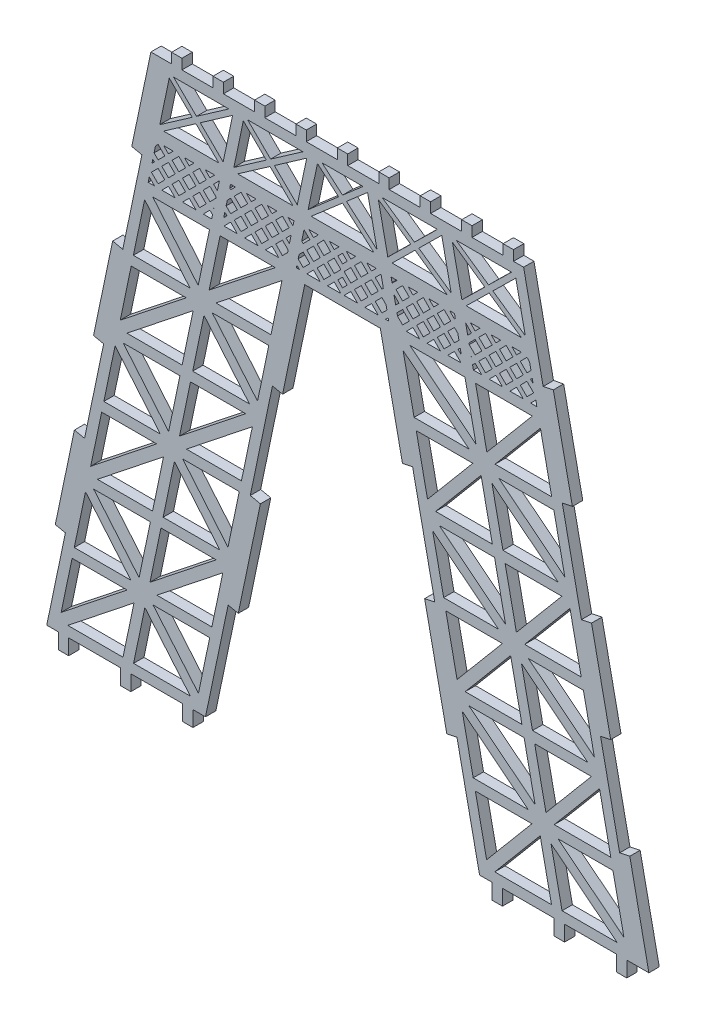
SolidWorks part; units mm, degrees
ref_plane "Front Plane" through (0, 0, 0) normal (0, 0, 1) x (1, 0, 0)
ref_plane "Top Plane" through (0, 0, 0) normal (0, 1, 0) x (1, 0, 0)
ref_plane "Right Plane" through (0, 0, 0) normal (1, 0, 0) x (0, 0, -1)
sketch "Sketch1" plane through (0, 0, 0) normal (0, 0, 1) x (1, 0, 0)
  line L2244 (350.4546, 229.6647) -> (353.6346, 244.8694)
  line L2245 (353.6346, 244.8694) -> (369.6113, 244.8694)
  line L2246 (369.6113, 244.8694) -> (350.4546, 229.6647)
  line L2247 (371.5439, 242.5732) -> (368.3725, 227.41)
  line L2248 (368.3725, 227.41) -> (352.4395, 227.41)
  line L2249 (352.4395, 227.41) -> (371.5439, 242.5732)
  line L2250 (327.9011, 224.41) -> (324.7297, 209.2469)
  line L2251 (324.7297, 209.2469) -> (343.8341, 224.41)
  line L2252 (343.8341, 224.41) -> (327.9011, 224.41)
  line L2253 (326.6623, 206.9506) -> (345.8191, 222.1554)
  line L2254 (345.8191, 222.1554) -> (342.639, 206.9506)
  line L2255 (342.639, 206.9506) -> (326.6623, 206.9506)
  line L2256 (341.8963, 188.7459) -> (345.0764, 203.9506)
  line L2257 (345.0764, 203.9506) -> (361.0531, 203.9506)
  line L2258 (361.0531, 203.9506) -> (341.8963, 188.7459)
  line L2259 (362.9857, 201.6544) -> (359.8143, 186.4912)
  line L2260 (359.8143, 186.4912) -> (343.8813, 186.4912)
  line L2261 (343.8813, 186.4912) -> (362.9857, 201.6544)
  line L2262 (319.3429, 183.4912) -> (316.1715, 168.3281)
  line L2263 (316.1715, 168.3281) -> (335.2759, 183.4912)
  line L2264 (335.2759, 183.4912) -> (319.3429, 183.4912)
  line L2265 (318.1041, 166.0318) -> (337.2608, 181.2366)
  line L2266 (337.2608, 181.2366) -> (334.0808, 166.0318)
  line L2267 (334.0808, 166.0318) -> (318.1041, 166.0318)
  line L2268 (333.3381, 147.8271) -> (336.5182, 163.0318)
  line L2269 (336.5182, 163.0318) -> (352.4949, 163.0318)
  line L2270 (352.4949, 163.0318) -> (333.3381, 147.8271)
  line L2271 (354.4274, 160.7356) -> (351.256, 145.5724)
  line L2272 (351.256, 145.5724) -> (335.3231, 145.5724)
  line L2273 (335.3231, 145.5724) -> (354.4274, 160.7356)
  line L2274 (310.7847, 142.5724) -> (307.6133, 127.4093)
  line L2275 (307.6133, 127.4093) -> (326.7177, 142.5724)
  line L2276 (326.7177, 142.5724) -> (310.7847, 142.5724)
  line L2277 (309.5459, 125.113) -> (328.7026, 140.3178)
  line L2278 (328.7026, 140.3178) -> (325.5225, 125.113)
  line L2279 (325.5225, 125.113) -> (309.5459, 125.113)
  line L2280 (345.0164, 125.113) -> (328.5875, 125.113)
  line L2281 (328.5875, 125.113) -> (331.8576, 140.7482)
  line L2282 (331.8576, 140.7482) -> (345.0164, 125.113)
  line L2283 (347.3672, 126.9789) -> (350.6286, 142.5724)
  line L2284 (350.6286, 142.5724) -> (334.2433, 142.5724)
  line L2285 (334.2433, 142.5724) -> (347.3672, 126.9789)
  line L2286 (317.0244, 163.0318) -> (333.4533, 163.0318)
  line L2287 (333.4533, 163.0318) -> (330.1832, 147.3967)
  line L2288 (330.1832, 147.3967) -> (317.0244, 163.0318)
  line L2289 (314.6736, 161.166) -> (311.4122, 145.5724)
  line L2290 (311.4122, 145.5724) -> (327.7974, 145.5724)
  line L2291 (327.7974, 145.5724) -> (314.6736, 161.166)
  line L2292 (353.5746, 166.0318) -> (337.1457, 166.0318)
  line L2293 (337.1457, 166.0318) -> (340.4158, 181.667)
  line L2294 (340.4158, 181.667) -> (353.5746, 166.0318)
  line L2295 (355.9254, 167.8977) -> (342.8016, 183.4912)
  line L2296 (342.8016, 183.4912) -> (359.1868, 183.4912)
  line L2297 (359.1868, 183.4912) -> (355.9254, 167.8977)
  line L2298 (325.5826, 203.9506) -> (342.0115, 203.9506)
  line L2299 (342.0115, 203.9506) -> (338.7414, 188.3155)
  line L2300 (338.7414, 188.3155) -> (325.5826, 203.9506)
  line L2301 (323.2318, 202.0848) -> (319.9704, 186.4912)
  line L2302 (319.9704, 186.4912) -> (336.3556, 186.4912)
  line L2303 (336.3556, 186.4912) -> (323.2318, 202.0848)
  line L2304 (362.1328, 206.9506) -> (345.7039, 206.9506)
  line L2305 (345.7039, 206.9506) -> (348.974, 222.5858)
  line L2306 (348.974, 222.5858) -> (362.1328, 206.9506)
  line L2307 (364.4836, 208.8164) -> (351.3598, 224.41)
  line L2308 (351.3598, 224.41) -> (367.745, 224.41)
  line L2309 (367.745, 224.41) -> (364.4836, 208.8164)
  line L2310 (334.1408, 244.8694) -> (350.5697, 244.8694)
  line L2311 (350.5697, 244.8694) -> (347.2996, 229.2343)
  line L2312 (347.2996, 229.2343) -> (334.1408, 244.8694)
  line L2313 (331.79, 243.0036) -> (328.5286, 227.41)
  line L2314 (328.5286, 227.41) -> (344.9138, 227.41)
  line L2315 (344.9138, 227.41) -> (331.79, 243.0036)
  line L2316 (347.8925, 270.3378) -> (357.262, 276.8665)
  line L2317 (357.262, 276.8665) -> (354.531, 263.8091)
  line L2318 (354.531, 263.8091) -> (347.8925, 270.3378)
  line L2319 (338.9138, 277.0641) -> (345.5523, 270.5354)
  line L2320 (345.5523, 270.5354) -> (336.1828, 264.0067)
  line L2321 (336.1828, 264.0067) -> (338.9138, 277.0641)
  line L2322 (353.2789, 262.9366) -> (337.2709, 262.9366)
  line L2323 (337.2709, 262.9366) -> (346.6404, 269.4653)
  line L2324 (346.6404, 269.4653) -> (353.2789, 262.9366)
  line L2325 (340.1659, 277.9366) -> (356.1739, 277.9366)
  line L2326 (356.1739, 277.9366) -> (346.8044, 271.4079)
  line L2327 (346.8044, 271.4079) -> (340.1659, 277.9366)
  line L2328 (367.0067, 270.5354) -> (357.6372, 264.0067)
  line L2329 (357.6372, 264.0067) -> (360.3682, 277.0641)
  line L2330 (360.3682, 277.0641) -> (367.0067, 270.5354)
  line L2331 (374.7333, 262.9366) -> (358.7253, 262.9366)
  line L2332 (358.7253, 262.9366) -> (368.0948, 269.4653)
  line L2333 (368.0948, 269.4653) -> (374.7333, 262.9366)
  line L2334 (369.3469, 270.3378) -> (378.7164, 276.8665)
  line L2335 (378.7164, 276.8665) -> (375.9854, 263.8091)
  line L2336 (375.9854, 263.8091) -> (369.3469, 270.3378)
  line L2337 (361.6203, 277.9366) -> (377.6283, 277.9366)
  line L2338 (377.6283, 277.9366) -> (368.2588, 271.4079)
  line L2339 (368.2588, 271.4079) -> (361.6203, 277.9366)
  line L2340 (387.9485, 271.7955) -> (379.1213, 264.1485)
  line L2341 (379.1213, 264.1485) -> (381.8294, 277.0965)
  line L2342 (381.8294, 277.0965) -> (387.9485, 271.7955)
  line L2343 (379.315, 259.3064) -> (382.0676, 259.3064)
  line L2344 (382.0676, 259.3064) -> (380.6913, 257.9301)
  line L2345 (380.6913, 257.9301) -> (379.315, 259.3064)
  line L2346 (386.6913, 257.9301) -> (385.315, 259.3064)
  line L2347 (385.315, 259.3064) -> (388.0676, 259.3064)
  line L2348 (388.0676, 259.3064) -> (386.6913, 257.9301)
  line L2349 (386.6913, 255.8088) -> (388.6306, 253.8694)
  line L2350 (388.6306, 253.8694) -> (386.6913, 251.9301)
  line L2351 (386.6913, 251.9301) -> (384.752, 253.8694)
  line L2352 (384.752, 253.8694) -> (386.6913, 255.8088)
  line L2353 (385.6306, 256.8694) -> (383.6913, 254.9301)
  line L2354 (383.6913, 254.9301) -> (381.752, 256.8694)
  line L2355 (381.752, 256.8694) -> (383.6913, 258.8088)
  line L2356 (383.6913, 258.8088) -> (385.6306, 256.8694)
  line L2357 (384.752, 247.8694) -> (386.6913, 249.8088)
  line L2358 (386.6913, 249.8088) -> (388.6306, 247.8694)
  line L2359 (388.6306, 247.8694) -> (384.752, 247.8694)
  line L2360 (381.752, 250.8694) -> (383.6913, 252.8088)
  line L2361 (383.6913, 252.8088) -> (385.6306, 250.8694)
  line L2362 (385.6306, 250.8694) -> (383.6913, 248.9301)
  line L2363 (383.6913, 248.9301) -> (381.752, 250.8694)
  line L2364 (378.752, 253.8694) -> (380.6913, 255.8088)
  line L2365 (380.6913, 255.8088) -> (382.6306, 253.8694)
  line L2366 (382.6306, 253.8694) -> (380.6913, 251.9301)
  line L2367 (380.6913, 251.9301) -> (378.752, 253.8694)
  line L2368 (373.315, 259.3064) -> (375.0436, 259.3064)
  line L2369 (375.0436, 259.3064) -> (374.7728, 258.0116)
  line L2370 (374.7728, 258.0116) -> (374.6913, 257.9301)
  line L2371 (374.6913, 257.9301) -> (373.315, 259.3064)
  line L2372 (377.2794, 255.342) -> (377.9503, 258.5498)
  line L2373 (377.9503, 258.5498) -> (379.6306, 256.8694)
  line L2374 (379.6306, 256.8694) -> (377.6913, 254.9301)
  line L2375 (377.6913, 254.9301) -> (377.2794, 255.342)
  line L2376 (376.6306, 247.8694) -> (375.7165, 247.8694)
  line L2377 (375.7165, 247.8694) -> (375.8746, 248.6255)
  line L2378 (375.8746, 248.6255) -> (376.6306, 247.8694)
  line L2379 (378.752, 247.8694) -> (380.6913, 249.8088)
  line L2380 (380.6913, 249.8088) -> (382.6306, 247.8694)
  line L2381 (382.6306, 247.8694) -> (378.752, 247.8694)
  line L2382 (376.2416, 250.3798) -> (376.5005, 251.618)
  line L2383 (376.5005, 251.618) -> (377.6913, 252.8088)
  line L2384 (377.6913, 252.8088) -> (379.6306, 250.8694)
  line L2385 (379.6306, 250.8694) -> (377.6913, 248.9301)
  line L2386 (377.6913, 248.9301) -> (376.2416, 250.3798)
  line L2387 (372.752, 253.8694) -> (374.2118, 255.3293)
  line L2388 (374.2118, 255.3293) -> (373.7068, 252.9146)
  line L2389 (373.7068, 252.9146) -> (372.752, 253.8694)
  line L2390 (369.752, 256.8694) -> (371.6913, 258.8088)
  line L2391 (371.6913, 258.8088) -> (373.6306, 256.8694)
  line L2392 (373.6306, 256.8694) -> (371.6913, 254.9301)
  line L2393 (371.6913, 254.9301) -> (369.752, 256.8694)
  line L2394 (367.315, 259.3064) -> (370.0676, 259.3064)
  line L2395 (370.0676, 259.3064) -> (368.6913, 257.9301)
  line L2396 (368.6913, 257.9301) -> (367.315, 259.3064)
  line L2397 (369.752, 250.8694) -> (371.6913, 252.8088)
  line L2398 (371.6913, 252.8088) -> (373.3399, 251.1602)
  line L2399 (373.3399, 251.1602) -> (373.186, 250.4248)
  line L2400 (373.186, 250.4248) -> (371.6913, 248.9301)
  line L2401 (371.6913, 248.9301) -> (369.752, 250.8694)
  line L2402 (366.752, 253.8694) -> (368.6913, 255.8088)
  line L2403 (368.6913, 255.8088) -> (370.6306, 253.8694)
  line L2404 (370.6306, 253.8694) -> (368.6913, 251.9301)
  line L2405 (368.6913, 251.9301) -> (366.752, 253.8694)
  line L2406 (363.752, 256.8694) -> (365.6913, 258.8088)
  line L2407 (365.6913, 258.8088) -> (367.6306, 256.8694)
  line L2408 (367.6306, 256.8694) -> (365.6913, 254.9301)
  line L2409 (365.6913, 254.9301) -> (363.752, 256.8694)
  line L2410 (361.315, 259.3064) -> (364.0676, 259.3064)
  line L2411 (364.0676, 259.3064) -> (362.6913, 257.9301)
  line L2412 (362.6913, 257.9301) -> (361.315, 259.3064)
  line L2413 (366.752, 247.8694) -> (368.6913, 249.8088)
  line L2414 (368.6913, 249.8088) -> (370.6306, 247.8694)
  line L2415 (370.6306, 247.8694) -> (366.752, 247.8694)
  line L2416 (363.752, 250.8694) -> (365.6913, 252.8088)
  line L2417 (365.6913, 252.8088) -> (367.6306, 250.8694)
  line L2418 (367.6306, 250.8694) -> (365.6913, 248.9301)
  line L2419 (365.6913, 248.9301) -> (363.752, 250.8694)
  line L2420 (360.752, 253.8694) -> (362.6913, 255.8088)
  line L2421 (362.6913, 255.8088) -> (364.6306, 253.8694)
  line L2422 (364.6306, 253.8694) -> (362.6913, 251.9301)
  line L2423 (362.6913, 251.9301) -> (360.752, 253.8694)
  line L2424 (357.752, 256.8694) -> (359.6913, 258.8088)
  line L2425 (359.6913, 258.8088) -> (361.6306, 256.8694)
  line L2426 (361.6306, 256.8694) -> (359.6913, 254.9301)
  line L2427 (359.6913, 254.9301) -> (357.752, 256.8694)
  line L2428 (356.4225, 258.1989) -> (356.6541, 259.3064)
  line L2429 (356.6541, 259.3064) -> (358.0676, 259.3064)
  line L2430 (358.0676, 259.3064) -> (356.6913, 257.9301)
  line L2431 (356.6913, 257.9301) -> (356.4225, 258.1989)
  line L2432 (355.6306, 250.8694) -> (354.6936, 249.9323)
  line L2433 (354.6936, 249.9323) -> (355.0177, 251.4823)
  line L2434 (355.0177, 251.4823) -> (355.6306, 250.8694)
  line L2435 (360.752, 247.8694) -> (362.6913, 249.8088)
  line L2436 (362.6913, 249.8088) -> (364.6306, 247.8694)
  line L2437 (364.6306, 247.8694) -> (360.752, 247.8694)
  line L2438 (357.752, 250.8694) -> (359.6913, 252.8088)
  line L2439 (359.6913, 252.8088) -> (361.6306, 250.8694)
  line L2440 (361.6306, 250.8694) -> (359.6913, 248.9301)
  line L2441 (359.6913, 248.9301) -> (357.752, 250.8694)
  line L2442 (355.3847, 253.2367) -> (355.7193, 254.8368)
  line L2443 (355.7193, 254.8368) -> (356.6913, 255.8088)
  line L2444 (356.6913, 255.8088) -> (358.6306, 253.8694)
  line L2445 (358.6306, 253.8694) -> (356.6913, 251.9301)
  line L2446 (356.6913, 251.9301) -> (355.3847, 253.2367)
  line L2447 (351.752, 256.8694) -> (353.4306, 258.5481)
  line L2448 (353.4306, 258.5481) -> (352.8499, 255.7715)
  line L2449 (352.8499, 255.7715) -> (351.752, 256.8694)
  line L2450 (349.315, 259.3064) -> (352.0676, 259.3064)
  line L2451 (352.0676, 259.3064) -> (350.6913, 257.9301)
  line L2452 (350.6913, 257.9301) -> (349.315, 259.3064)
  line L2453 (354.752, 247.8694) -> (356.6913, 249.8088)
  line L2454 (356.6913, 249.8088) -> (358.6306, 247.8694)
  line L2455 (358.6306, 247.8694) -> (354.752, 247.8694)
  line L2456 (351.752, 250.8694) -> (351.8439, 250.9613)
  line L2457 (351.8439, 250.9613) -> (351.8121, 250.8093)
  line L2458 (351.8121, 250.8093) -> (351.752, 250.8694)
  line L2459 (348.752, 253.8694) -> (350.6913, 255.8088)
  line L2460 (350.6913, 255.8088) -> (352.483, 254.0171)
  line L2461 (352.483, 254.0171) -> (352.4049, 253.6437)
  line L2462 (352.4049, 253.6437) -> (350.6913, 251.9301)
  line L2463 (350.6913, 251.9301) -> (348.752, 253.8694)
  line L2464 (345.752, 256.8694) -> (347.6913, 258.8088)
  line L2465 (347.6913, 258.8088) -> (349.6306, 256.8694)
  line L2466 (349.6306, 256.8694) -> (347.6913, 254.9301)
  line L2467 (347.6913, 254.9301) -> (345.752, 256.8694)
  line L2468 (343.315, 259.3064) -> (346.0676, 259.3064)
  line L2469 (346.0676, 259.3064) -> (344.6913, 257.9301)
  line L2470 (344.6913, 257.9301) -> (343.315, 259.3064)
  line L2471 (348.752, 247.8694) -> (350.6913, 249.8088)
  line L2472 (350.6913, 249.8088) -> (351.4451, 249.0549)
  line L2473 (351.4451, 249.0549) -> (351.1972, 247.8694)
  line L2474 (351.1972, 247.8694) -> (348.752, 247.8694)
  line L2475 (345.752, 250.8694) -> (347.6913, 252.8088)
  line L2476 (347.6913, 252.8088) -> (349.6306, 250.8694)
  line L2477 (349.6306, 250.8694) -> (347.6913, 248.9301)
  line L2478 (347.6913, 248.9301) -> (345.752, 250.8694)
  line L2479 (342.752, 253.8694) -> (344.6913, 255.8088)
  line L2480 (344.6913, 255.8088) -> (346.6306, 253.8694)
  line L2481 (346.6306, 253.8694) -> (344.6913, 251.9301)
  line L2482 (344.6913, 251.9301) -> (342.752, 253.8694)
  line L2483 (339.752, 256.8694) -> (341.6913, 258.8088)
  line L2484 (341.6913, 258.8088) -> (343.6306, 256.8694)
  line L2485 (343.6306, 256.8694) -> (341.6913, 254.9301)
  line L2486 (341.6913, 254.9301) -> (339.752, 256.8694)
  line L2487 (337.315, 259.3064) -> (340.0676, 259.3064)
  line L2488 (340.0676, 259.3064) -> (338.6913, 257.9301)
  line L2489 (338.6913, 257.9301) -> (337.315, 259.3064)
  line L2490 (342.752, 247.8694) -> (344.6913, 249.8088)
  line L2491 (344.6913, 249.8088) -> (346.6306, 247.8694)
  line L2492 (346.6306, 247.8694) -> (342.752, 247.8694)
  line L2493 (339.752, 250.8694) -> (341.6913, 252.8088)
  line L2494 (341.6913, 252.8088) -> (343.6306, 250.8694)
  line L2495 (343.6306, 250.8694) -> (341.6913, 248.9301)
  line L2496 (341.6913, 248.9301) -> (339.752, 250.8694)
  line L2497 (336.752, 253.8694) -> (338.6913, 255.8088)
  line L2498 (338.6913, 255.8088) -> (340.6306, 253.8694)
  line L2499 (340.6306, 253.8694) -> (338.6913, 251.9301)
  line L2500 (338.6913, 251.9301) -> (336.752, 253.8694)
  line L2501 (334.5278, 256.0936) -> (334.9382, 258.0556)
  line L2502 (334.9382, 258.0556) -> (335.6913, 258.8088)
  line L2503 (335.6913, 258.8088) -> (337.6306, 256.8694)
  line L2504 (337.6306, 256.8694) -> (335.6913, 254.9301)
  line L2505 (335.6913, 254.9301) -> (334.5278, 256.0936)
  line L2506 (334.1609, 254.3392) -> (334.6306, 253.8694)
  line L2507 (334.6306, 253.8694) -> (333.9124, 253.1512)
  line L2508 (333.9124, 253.1512) -> (334.1609, 254.3392)
  line L2509 (336.752, 247.8694) -> (338.6913, 249.8088)
  line L2510 (338.6913, 249.8088) -> (340.6306, 247.8694)
  line L2511 (340.6306, 247.8694) -> (336.752, 247.8694)
  line L2512 (333.752, 250.8694) -> (335.6913, 252.8088)
  line L2513 (335.6913, 252.8088) -> (337.6306, 250.8694)
  line L2514 (337.6306, 250.8694) -> (335.6913, 248.9301)
  line L2515 (335.6913, 248.9301) -> (333.752, 250.8694)
  line L2516 (332.8077, 247.8694) -> (334.6306, 247.8694)
  line L2517 (334.6306, 247.8694) -> (333.123, 249.3771)
  line L2518 (333.123, 249.3771) -> (332.8077, 247.8694)
  line L2519 (427.7333, 229.6647) -> (424.5532, 244.8694)
  line L2520 (424.5532, 244.8694) -> (408.5765, 244.8694)
  line L2521 (408.5765, 244.8694) -> (427.7333, 229.6647)
  line L2522 (425.7483, 227.41) -> (409.8153, 227.41)
  line L2523 (409.8153, 227.41) -> (406.644, 242.5732)
  line L2524 (406.644, 242.5732) -> (425.7483, 227.41)
  line L2525 (434.3537, 224.41) -> (453.4581, 209.2469)
  line L2526 (453.4581, 209.2469) -> (450.2867, 224.41)
  line L2527 (450.2867, 224.41) -> (434.3537, 224.41)
  line L2528 (451.5255, 206.9506) -> (432.3688, 222.1554)
  line L2529 (432.3688, 222.1554) -> (435.5489, 206.9506)
  line L2530 (435.5489, 206.9506) -> (451.5255, 206.9506)
  line L2531 (436.2915, 188.7459) -> (433.1114, 203.9506)
  line L2532 (433.1114, 203.9506) -> (417.1347, 203.9506)
  line L2533 (417.1347, 203.9506) -> (436.2915, 188.7459)
  line L2534 (434.3065, 186.4912) -> (418.3736, 186.4912)
  line L2535 (418.3736, 186.4912) -> (415.2022, 201.6544)
  line L2536 (415.2022, 201.6544) -> (434.3065, 186.4912)
  line L2537 (442.9119, 183.4912) -> (462.0163, 168.3281)
  line L2538 (462.0163, 168.3281) -> (458.8449, 183.4912)
  line L2539 (458.8449, 183.4912) -> (442.9119, 183.4912)
  line L2540 (460.0837, 166.0318) -> (440.927, 181.2366)
  line L2541 (440.927, 181.2366) -> (444.1071, 166.0318)
  line L2542 (444.1071, 166.0318) -> (460.0837, 166.0318)
  line L2543 (444.8497, 147.8271) -> (441.6696, 163.0318)
  line L2544 (441.6696, 163.0318) -> (425.6929, 163.0318)
  line L2545 (425.6929, 163.0318) -> (444.8497, 147.8271)
  line L2546 (442.8648, 145.5724) -> (426.9318, 145.5724)
  line L2547 (426.9318, 145.5724) -> (423.7604, 160.7356)
  line L2548 (423.7604, 160.7356) -> (442.8648, 145.5724)
  line L2549 (451.4701, 142.5724) -> (470.5745, 127.4093)
  line L2550 (470.5745, 127.4093) -> (467.4031, 142.5724)
  line L2551 (467.4031, 142.5724) -> (451.4701, 142.5724)
  line L2552 (468.642, 125.113) -> (449.4852, 140.3178)
  line L2553 (449.4852, 140.3178) -> (452.6653, 125.113)
  line L2554 (452.6653, 125.113) -> (468.642, 125.113)
  line L2555 (446.3303, 140.7482) -> (449.6004, 125.113)
  line L2556 (449.6004, 125.113) -> (433.1714, 125.113)
  line L2557 (433.1714, 125.113) -> (446.3303, 140.7482)
  line L2558 (443.9445, 142.5724) -> (427.5592, 142.5724)
  line L2559 (427.5592, 142.5724) -> (430.8206, 126.9789)
  line L2560 (430.8206, 126.9789) -> (443.9445, 142.5724)
  line L2561 (461.1635, 163.0318) -> (444.7345, 163.0318)
  line L2562 (444.7345, 163.0318) -> (448.0046, 147.3967)
  line L2563 (448.0046, 147.3967) -> (461.1635, 163.0318)
  line L2564 (450.3904, 145.5724) -> (466.7757, 145.5724)
  line L2565 (466.7757, 145.5724) -> (463.5142, 161.166)
  line L2566 (463.5142, 161.166) -> (450.3904, 145.5724)
  line L2567 (424.6132, 166.0318) -> (441.0422, 166.0318)
  line L2568 (441.0422, 166.0318) -> (437.772, 181.667)
  line L2569 (437.772, 181.667) -> (424.6132, 166.0318)
  line L2570 (422.2624, 167.8977) -> (435.3863, 183.4912)
  line L2571 (435.3863, 183.4912) -> (419.001, 183.4912)
  line L2572 (419.001, 183.4912) -> (422.2624, 167.8977)
  line L2573 (452.6052, 203.9506) -> (436.1763, 203.9506)
  line L2574 (436.1763, 203.9506) -> (439.4464, 188.3155)
  line L2575 (439.4464, 188.3155) -> (452.6052, 203.9506)
  line L2576 (441.8322, 186.4912) -> (458.2174, 186.4912)
  line L2577 (458.2174, 186.4912) -> (454.956, 202.0848)
  line L2578 (454.956, 202.0848) -> (441.8322, 186.4912)
  line L2579 (416.055, 206.9506) -> (432.4839, 206.9506)
  line L2580 (432.4839, 206.9506) -> (429.2138, 222.5858)
  line L2581 (429.2138, 222.5858) -> (416.055, 206.9506)
  line L2582 (413.7042, 208.8164) -> (426.828, 224.41)
  line L2583 (426.828, 224.41) -> (410.4428, 224.41)
  line L2584 (410.4428, 224.41) -> (413.7042, 208.8164)
  line L2585 (444.047, 244.8694) -> (427.6181, 244.8694)
  line L2586 (427.6181, 244.8694) -> (430.8882, 229.2343)
  line L2587 (430.8882, 229.2343) -> (444.047, 244.8694)
  line L2588 (433.274, 227.41) -> (449.6592, 227.41)
  line L2589 (449.6592, 227.41) -> (446.3978, 243.0036)
  line L2590 (446.3978, 243.0036) -> (433.274, 227.41)
  line L2591 (430.2954, 270.3378) -> (420.9259, 276.8665)
  line L2592 (420.9259, 276.8665) -> (423.6568, 263.8091)
  line L2593 (423.6568, 263.8091) -> (430.2954, 270.3378)
  line L2594 (439.274, 277.0641) -> (432.6355, 270.5354)
  line L2595 (432.6355, 270.5354) -> (442.005, 264.0067)
  line L2596 (442.005, 264.0067) -> (439.274, 277.0641)
  line L2597 (424.9089, 262.9366) -> (440.9169, 262.9366)
  line L2598 (440.9169, 262.9366) -> (431.5474, 269.4653)
  line L2599 (431.5474, 269.4653) -> (424.9089, 262.9366)
  line L2600 (431.3834, 271.4079) -> (422.0139, 277.9366)
  line L2601 (422.0139, 277.9366) -> (438.0219, 277.9366)
  line L2602 (438.0219, 277.9366) -> (431.3834, 271.4079)
  line L2603 (411.1811, 270.5354) -> (420.5506, 264.0067)
  line L2604 (420.5506, 264.0067) -> (417.8196, 277.0641)
  line L2605 (417.8196, 277.0641) -> (411.1811, 270.5354)
  line L2606 (403.4545, 262.9366) -> (419.4625, 262.9366)
  line L2607 (419.4625, 262.9366) -> (410.093, 269.4653)
  line L2608 (410.093, 269.4653) -> (403.4545, 262.9366)
  line L2609 (408.841, 270.3378) -> (399.4715, 276.8665)
  line L2610 (399.4715, 276.8665) -> (402.2024, 263.8091)
  line L2611 (402.2024, 263.8091) -> (408.841, 270.3378)
  line L2612 (409.929, 271.4079) -> (400.5595, 277.9366)
  line L2613 (400.5595, 277.9366) -> (416.5675, 277.9366)
  line L2614 (416.5675, 277.9366) -> (409.929, 271.4079)
  line L2615 (390.2393, 271.7955) -> (399.0665, 264.1485)
  line L2616 (399.0665, 264.1485) -> (396.3584, 277.0965)
  line L2617 (396.3584, 277.0965) -> (390.2393, 271.7955)
  line L2618 (398.8728, 259.3064) -> (396.1202, 259.3064)
  line L2619 (396.1202, 259.3064) -> (397.4965, 257.9301)
  line L2620 (397.4965, 257.9301) -> (398.8728, 259.3064)
  line L2621 (390.4359, 250.8694) -> (389.0939, 252.2114)
  line L2622 (389.0939, 252.2114) -> (387.752, 250.8694)
  line L2623 (387.752, 250.8694) -> (389.0939, 249.5275)
  line L2624 (389.0939, 249.5275) -> (390.4359, 250.8694)
  line L2625 (391.4965, 257.9301) -> (392.8728, 259.3064)
  line L2626 (392.8728, 259.3064) -> (390.1202, 259.3064)
  line L2627 (390.1202, 259.3064) -> (391.4965, 257.9301)
  line L2628 (391.4965, 255.8088) -> (389.5572, 253.8694)
  line L2629 (389.5572, 253.8694) -> (391.4965, 251.9301)
  line L2630 (391.4965, 251.9301) -> (393.4359, 253.8694)
  line L2631 (393.4359, 253.8694) -> (391.4965, 255.8088)
  line L2632 (392.5572, 256.8694) -> (394.4965, 254.9301)
  line L2633 (394.4965, 254.9301) -> (396.4359, 256.8694)
  line L2634 (396.4359, 256.8694) -> (394.4965, 258.8088)
  line L2635 (394.4965, 258.8088) -> (392.5572, 256.8694)
  line L2636 (393.4359, 247.8694) -> (391.4965, 249.8088)
  line L2637 (391.4965, 249.8088) -> (389.5572, 247.8694)
  line L2638 (389.5572, 247.8694) -> (393.4359, 247.8694)
  line L2639 (396.4359, 250.8694) -> (394.4965, 252.8088)
  line L2640 (394.4965, 252.8088) -> (392.5572, 250.8694)
  line L2641 (392.5572, 250.8694) -> (394.4965, 248.9301)
  line L2642 (394.4965, 248.9301) -> (396.4359, 250.8694)
  line L2643 (399.4359, 253.8694) -> (397.4965, 255.8088)
  line L2644 (397.4965, 255.8088) -> (395.5572, 253.8694)
  line L2645 (395.5572, 253.8694) -> (397.4965, 251.9301)
  line L2646 (397.4965, 251.9301) -> (399.4359, 253.8694)
  line L2647 (404.8728, 259.3064) -> (403.1442, 259.3064)
  line L2648 (403.1442, 259.3064) -> (403.415, 258.0116)
  line L2649 (403.415, 258.0116) -> (403.4965, 257.9301)
  line L2650 (403.4965, 257.9301) -> (404.8728, 259.3064)
  line L2651 (400.9084, 255.342) -> (400.2375, 258.5498)
  line L2652 (400.2375, 258.5498) -> (398.5572, 256.8694)
  line L2653 (398.5572, 256.8694) -> (400.4965, 254.9301)
  line L2654 (400.4965, 254.9301) -> (400.9084, 255.342)
  line L2655 (402.3132, 248.6255) -> (402.4713, 247.8694)
  line L2656 (402.4713, 247.8694) -> (401.5572, 247.8694)
  line L2657 (401.5572, 247.8694) -> (402.3132, 248.6255)
  line L2658 (399.4359, 247.8694) -> (397.4965, 249.8088)
  line L2659 (397.4965, 249.8088) -> (395.5572, 247.8694)
  line L2660 (395.5572, 247.8694) -> (399.4359, 247.8694)
  line L2661 (401.9463, 250.3798) -> (401.6873, 251.618)
  line L2662 (401.6873, 251.618) -> (400.4965, 252.8088)
  line L2663 (400.4965, 252.8088) -> (398.5572, 250.8694)
  line L2664 (398.5572, 250.8694) -> (400.4965, 248.9301)
  line L2665 (400.4965, 248.9301) -> (401.9463, 250.3798)
  line L2666 (405.4359, 253.8694) -> (403.976, 255.3293)
  line L2667 (403.976, 255.3293) -> (404.481, 252.9146)
  line L2668 (404.481, 252.9146) -> (405.4359, 253.8694)
  line L2669 (408.4359, 256.8694) -> (406.4965, 258.8088)
  line L2670 (406.4965, 258.8088) -> (404.5572, 256.8694)
  line L2671 (404.5572, 256.8694) -> (406.4965, 254.9301)
  line L2672 (406.4965, 254.9301) -> (408.4359, 256.8694)
  line L2673 (410.8728, 259.3064) -> (408.1202, 259.3064)
  line L2674 (408.1202, 259.3064) -> (409.4965, 257.9301)
  line L2675 (409.4965, 257.9301) -> (410.8728, 259.3064)
  line L2676 (408.4359, 250.8694) -> (406.4965, 252.8088)
  line L2677 (406.4965, 252.8088) -> (404.848, 251.1602)
  line L2678 (404.848, 251.1602) -> (405.0018, 250.4248)
  line L2679 (405.0018, 250.4248) -> (406.4965, 248.9301)
  line L2680 (406.4965, 248.9301) -> (408.4359, 250.8694)
  line L2681 (411.4359, 253.8694) -> (409.4965, 255.8088)
  line L2682 (409.4965, 255.8088) -> (407.5572, 253.8694)
  line L2683 (407.5572, 253.8694) -> (409.4965, 251.9301)
  line L2684 (409.4965, 251.9301) -> (411.4359, 253.8694)
  line L2685 (414.4359, 256.8694) -> (412.4965, 258.8088)
  line L2686 (412.4965, 258.8088) -> (410.5572, 256.8694)
  line L2687 (410.5572, 256.8694) -> (412.4965, 254.9301)
  line L2688 (412.4965, 254.9301) -> (414.4359, 256.8694)
  line L2689 (416.8728, 259.3064) -> (414.1202, 259.3064)
  line L2690 (414.1202, 259.3064) -> (415.4965, 257.9301)
  line L2691 (415.4965, 257.9301) -> (416.8728, 259.3064)
  line L2692 (411.4359, 247.8694) -> (409.4965, 249.8088)
  line L2693 (409.4965, 249.8088) -> (407.5572, 247.8694)
  line L2694 (407.5572, 247.8694) -> (411.4359, 247.8694)
  line L2695 (414.4359, 250.8694) -> (412.4965, 252.8088)
  line L2696 (412.4965, 252.8088) -> (410.5572, 250.8694)
  line L2697 (410.5572, 250.8694) -> (412.4965, 248.9301)
  line L2698 (412.4965, 248.9301) -> (414.4359, 250.8694)
  line L2699 (417.4359, 253.8694) -> (415.4965, 255.8088)
  line L2700 (415.4965, 255.8088) -> (413.5572, 253.8694)
  line L2701 (413.5572, 253.8694) -> (415.4965, 251.9301)
  line L2702 (415.4965, 251.9301) -> (417.4359, 253.8694)
  line L2703 (420.4359, 256.8694) -> (418.4965, 258.8088)
  line L2704 (418.4965, 258.8088) -> (416.5572, 256.8694)
  line L2705 (416.5572, 256.8694) -> (418.4965, 254.9301)
  line L2706 (418.4965, 254.9301) -> (420.4359, 256.8694)
  line L2707 (421.7653, 258.1989) -> (421.5337, 259.3064)
  line L2708 (421.5337, 259.3064) -> (420.1202, 259.3064)
  line L2709 (420.1202, 259.3064) -> (421.4965, 257.9301)
  line L2710 (421.4965, 257.9301) -> (421.7653, 258.1989)
  line L2711 (422.5572, 250.8694) -> (423.4943, 249.9323)
  line L2712 (423.4943, 249.9323) -> (423.1701, 251.4823)
  line L2713 (423.1701, 251.4823) -> (422.5572, 250.8694)
  line L2714 (417.4359, 247.8694) -> (415.4965, 249.8088)
  line L2715 (415.4965, 249.8088) -> (413.5572, 247.8694)
  line L2716 (413.5572, 247.8694) -> (417.4359, 247.8694)
  line L2717 (420.4359, 250.8694) -> (418.4965, 252.8088)
  line L2718 (418.4965, 252.8088) -> (416.5572, 250.8694)
  line L2719 (416.5572, 250.8694) -> (418.4965, 248.9301)
  line L2720 (418.4965, 248.9301) -> (420.4359, 250.8694)
  line L2721 (422.8031, 253.2367) -> (422.4685, 254.8368)
  line L2722 (422.4685, 254.8368) -> (421.4965, 255.8088)
  line L2723 (421.4965, 255.8088) -> (419.5572, 253.8694)
  line L2724 (419.5572, 253.8694) -> (421.4965, 251.9301)
  line L2725 (421.4965, 251.9301) -> (422.8031, 253.2367)
  line L2726 (426.4359, 256.8694) -> (424.7572, 258.5481)
  line L2727 (424.7572, 258.5481) -> (425.3379, 255.7715)
  line L2728 (425.3379, 255.7715) -> (426.4359, 256.8694)
  line L2729 (428.8728, 259.3064) -> (426.1202, 259.3064)
  line L2730 (426.1202, 259.3064) -> (427.4965, 257.9301)
  line L2731 (427.4965, 257.9301) -> (428.8728, 259.3064)
  line L2732 (423.4359, 247.8694) -> (421.4965, 249.8088)
  line L2733 (421.4965, 249.8088) -> (419.5572, 247.8694)
  line L2734 (419.5572, 247.8694) -> (423.4359, 247.8694)
  line L2735 (426.4359, 250.8694) -> (426.344, 250.9613)
  line L2736 (426.344, 250.9613) -> (426.3758, 250.8093)
  line L2737 (426.3758, 250.8093) -> (426.4359, 250.8694)
  line L2738 (429.4359, 253.8694) -> (427.4965, 255.8088)
  line L2739 (427.4965, 255.8088) -> (425.7048, 254.0171)
  line L2740 (425.7048, 254.0171) -> (425.783, 253.6437)
  line L2741 (425.783, 253.6437) -> (427.4965, 251.9301)
  line L2742 (427.4965, 251.9301) -> (429.4359, 253.8694)
  line L2743 (432.4359, 256.8694) -> (430.4965, 258.8088)
  line L2744 (430.4965, 258.8088) -> (428.5572, 256.8694)
  line L2745 (428.5572, 256.8694) -> (430.4965, 254.9301)
  line L2746 (430.4965, 254.9301) -> (432.4359, 256.8694)
  line L2747 (434.8728, 259.3064) -> (432.1202, 259.3064)
  line L2748 (432.1202, 259.3064) -> (433.4965, 257.9301)
  line L2749 (433.4965, 257.9301) -> (434.8728, 259.3064)
  line L2750 (429.4359, 247.8694) -> (427.4965, 249.8088)
  line L2751 (427.4965, 249.8088) -> (426.7427, 249.0549)
  line L2752 (426.7427, 249.0549) -> (426.9906, 247.8694)
  line L2753 (426.9906, 247.8694) -> (429.4359, 247.8694)
  line L2754 (432.4359, 250.8694) -> (430.4965, 252.8088)
  line L2755 (430.4965, 252.8088) -> (428.5572, 250.8694)
  line L2756 (428.5572, 250.8694) -> (430.4965, 248.9301)
  line L2757 (430.4965, 248.9301) -> (432.4359, 250.8694)
  line L2758 (435.4359, 253.8694) -> (433.4965, 255.8088)
  line L2759 (433.4965, 255.8088) -> (431.5572, 253.8694)
  line L2760 (431.5572, 253.8694) -> (433.4965, 251.9301)
  line L2761 (433.4965, 251.9301) -> (435.4359, 253.8694)
  line L2762 (438.4359, 256.8694) -> (436.4965, 258.8088)
  line L2763 (436.4965, 258.8088) -> (434.5572, 256.8694)
  line L2764 (434.5572, 256.8694) -> (436.4965, 254.9301)
  line L2765 (436.4965, 254.9301) -> (438.4359, 256.8694)
  line L2766 (440.8728, 259.3064) -> (438.1202, 259.3064)
  line L2767 (438.1202, 259.3064) -> (439.4965, 257.9301)
  line L2768 (439.4965, 257.9301) -> (440.8728, 259.3064)
  line L2769 (435.4359, 247.8694) -> (433.4965, 249.8088)
  line L2770 (433.4965, 249.8088) -> (431.5572, 247.8694)
  line L2771 (431.5572, 247.8694) -> (435.4359, 247.8694)
  line L2772 (438.4359, 250.8694) -> (436.4965, 252.8088)
  line L2773 (436.4965, 252.8088) -> (434.5572, 250.8694)
  line L2774 (434.5572, 250.8694) -> (436.4965, 248.9301)
  line L2775 (436.4965, 248.9301) -> (438.4359, 250.8694)
  line L2776 (441.4359, 253.8694) -> (439.4965, 255.8088)
  line L2777 (439.4965, 255.8088) -> (437.5572, 253.8694)
  line L2778 (437.5572, 253.8694) -> (439.4965, 251.9301)
  line L2779 (439.4965, 251.9301) -> (441.4359, 253.8694)
  line L2780 (442.4965, 254.9301) -> (440.5572, 256.8694)
  line L2781 (440.5572, 256.8694) -> (442.4965, 258.8088)
  line L2782 (442.4965, 258.8088) -> (443.2497, 258.0556)
  line L2783 (443.2497, 258.0556) -> (443.66, 256.0936)
  line L2784 (443.66, 256.0936) -> (442.4965, 254.9301)
  line L2785 (444.027, 254.3392) -> (443.5572, 253.8694)
  line L2786 (443.5572, 253.8694) -> (444.2754, 253.1512)
  line L2787 (444.2754, 253.1512) -> (444.027, 254.3392)
  line L2788 (441.4359, 247.8694) -> (439.4965, 249.8088)
  line L2789 (439.4965, 249.8088) -> (437.5572, 247.8694)
  line L2790 (437.5572, 247.8694) -> (441.4359, 247.8694)
  line L2791 (444.4359, 250.8694) -> (442.4965, 252.8088)
  line L2792 (442.4965, 252.8088) -> (440.5572, 250.8694)
  line L2793 (440.5572, 250.8694) -> (442.4965, 248.9301)
  line L2794 (442.4965, 248.9301) -> (444.4359, 250.8694)
  line L2795 (445.0648, 249.3771) -> (443.5572, 247.8694)
  line L2796 (443.5572, 247.8694) -> (445.3801, 247.8694)
  line L2797 (445.3801, 247.8694) -> (445.0648, 249.3771)
  line L2798 (380.0132, 262.9366) -> (398.1746, 262.9366)
  line L2799 (398.1746, 262.9366) -> (389.0939, 270.8032)
  line L2800 (389.0939, 270.8032) -> (380.0132, 262.9366)
  line L2801 (389.0939, 272.7878) -> (395.0373, 277.9366)
  line L2802 (395.0373, 277.9366) -> (383.1505, 277.9366)
  line L2803 (383.1505, 277.9366) -> (389.0939, 272.7878)
  line L2804 (389.0939, 258.2114) -> (390.4359, 256.8694)
  line L2805 (390.4359, 256.8694) -> (389.0939, 255.5275)
  line L2806 (389.0939, 255.5275) -> (387.752, 256.8694)
  line L2807 (387.752, 256.8694) -> (389.0939, 258.2114)
  line L2808 (471.3995, 122.113) -> (471.3995, 117.613)
  line L2809 (471.3995, 117.613) -> (468.3995, 117.613)
  line L2810 (468.3995, 117.613) -> (468.3995, 122.113)
  line L2811 (468.3995, 122.113) -> (453.3995, 122.113)
  line L2812 (453.3995, 122.113) -> (453.3995, 117.613)
  line L2813 (453.3995, 117.613) -> (450.3995, 117.613)
  line L2814 (450.3995, 117.613) -> (450.3995, 122.113)
  line L2815 (450.3995, 122.113) -> (435.3995, 122.113)
  line L2816 (435.3995, 122.113) -> (435.3995, 117.613)
  line L2817 (435.3995, 117.613) -> (432.3995, 117.613)
  line L2818 (432.3995, 117.613) -> (432.3995, 122.113)
  line L2819 (432.3995, 122.113) -> (428.7734, 122.113)
  line L2820 (428.7734, 122.113) -> (422.2263, 153.4163)
  line L2821 (422.2263, 153.4163) -> (419.2898, 152.8021)
  line L2822 (419.2898, 152.8021) -> (412.8712, 183.4912)
  line L2823 (412.8712, 183.4912) -> (415.8076, 184.1054)
  line L2824 (415.8076, 184.1054) -> (409.389, 214.7945)
  line L2825 (409.389, 214.7945) -> (406.4525, 214.1803)
  line L2826 (406.4525, 214.1803) -> (400.0339, 244.8694)
  line L2827 (400.0339, 244.8694) -> (378.154, 244.8694)
  line L2828 (378.154, 244.8694) -> (371.7353, 214.1803)
  line L2829 (371.7353, 214.1803) -> (368.7988, 214.7945)
  line L2830 (368.7988, 214.7945) -> (362.3802, 184.1054)
  line L2831 (362.3802, 184.1054) -> (365.3166, 183.4912)
  line L2832 (365.3166, 183.4912) -> (358.898, 152.8021)
  line L2833 (358.898, 152.8021) -> (355.9615, 153.4163)
  line L2834 (355.9615, 153.4163) -> (349.4144, 122.113)
  line L2835 (349.4144, 122.113) -> (345.7883, 122.113)
  line L2836 (345.7883, 122.113) -> (345.7883, 117.613)
  line L2837 (345.7883, 117.613) -> (342.7883, 117.613)
  line L2838 (342.7883, 117.613) -> (342.7883, 122.113)
  line L2839 (342.7883, 122.113) -> (327.7883, 122.113)
  line L2840 (327.7883, 122.113) -> (327.7883, 117.613)
  line L2841 (327.7883, 117.613) -> (324.7883, 117.613)
  line L2842 (324.7883, 117.613) -> (324.7883, 122.113)
  line L2843 (324.7883, 122.113) -> (309.7883, 122.113)
  line L2844 (309.7883, 122.113) -> (309.7883, 117.613)
  line L2845 (309.7883, 117.613) -> (306.7883, 117.613)
  line L2846 (306.7883, 117.613) -> (306.7883, 122.113)
  line L2847 (306.7883, 122.113) -> (303.4407, 122.113)
  line L2848 (303.4407, 122.113) -> (308.8486, 147.9695)
  line L2849 (308.8486, 147.9695) -> (305.9121, 148.5836)
  line L2850 (305.9121, 148.5836) -> (311.4485, 175.0542)
  line L2851 (311.4485, 175.0542) -> (314.3849, 174.4401)
  line L2852 (314.3849, 174.4401) -> (319.9213, 200.9107)
  line L2853 (319.9213, 200.9107) -> (316.9848, 201.5248)
  line L2854 (316.9848, 201.5248) -> (322.5212, 227.9954)
  line L2855 (322.5212, 227.9954) -> (325.4577, 227.3813)
  line L2856 (325.4577, 227.3813) -> (330.994, 253.8519)
  line L2857 (330.994, 253.8519) -> (328.0576, 254.466)
  line L2858 (328.0576, 254.466) -> (333.5939, 280.9366)
  line L2859 (333.5939, 280.9366) -> (339.5939, 280.9366)
  line L2860 (339.5939, 280.9366) -> (339.5939, 283.8694)
  line L2861 (339.5939, 283.8694) -> (342.5939, 283.8694)
  line L2862 (342.5939, 283.8694) -> (342.5939, 280.9366)
  line L2863 (342.5939, 280.9366) -> (351.5939, 280.9366)
  line L2864 (351.5939, 280.9366) -> (351.5939, 283.8694)
  line L2865 (351.5939, 283.8694) -> (354.5939, 283.8694)
  line L2866 (354.5939, 283.8694) -> (354.5939, 280.9366)
  line L2867 (354.5939, 280.9366) -> (363.5939, 280.9366)
  line L2868 (363.5939, 280.9366) -> (363.5939, 283.8694)
  line L2869 (363.5939, 283.8694) -> (366.5939, 283.8694)
  line L2870 (366.5939, 283.8694) -> (366.5939, 280.9366)
  line L2871 (366.5939, 280.9366) -> (375.5939, 280.9366)
  line L2872 (375.5939, 280.9366) -> (375.5939, 283.8694)
  line L2873 (375.5939, 283.8694) -> (378.5939, 283.8694)
  line L2874 (378.5939, 283.8694) -> (378.5939, 280.9366)
  line L2875 (378.5939, 280.9366) -> (387.5939, 280.9366)
  line L2876 (387.5939, 280.9366) -> (387.5939, 283.8694)
  line L2877 (387.5939, 283.8694) -> (390.5939, 283.8694)
  line L2878 (390.5939, 283.8694) -> (390.5939, 280.9366)
  line L2879 (390.5939, 280.9366) -> (399.5939, 280.9366)
  line L2880 (399.5939, 280.9366) -> (399.5939, 283.8694)
  line L2881 (399.5939, 283.8694) -> (402.5939, 283.8694)
  line L2882 (402.5939, 283.8694) -> (402.5939, 280.9366)
  line L2883 (402.5939, 280.9366) -> (411.5939, 280.9366)
  line L2884 (411.5939, 280.9366) -> (411.5939, 283.8694)
  line L2885 (411.5939, 283.8694) -> (414.5939, 283.8694)
  line L2886 (414.5939, 283.8694) -> (414.5939, 280.9366)
  line L2887 (414.5939, 280.9366) -> (423.5939, 280.9366)
  line L2888 (423.5939, 280.9366) -> (423.5939, 283.8694)
  line L2889 (423.5939, 283.8694) -> (426.5939, 283.8694)
  line L2890 (426.5939, 283.8694) -> (426.5939, 280.9366)
  line L2891 (426.5939, 280.9366) -> (435.5939, 280.9366)
  line L2892 (435.5939, 280.9366) -> (435.5939, 283.8694)
  line L2893 (435.5939, 283.8694) -> (438.5939, 283.8694)
  line L2894 (438.5939, 283.8694) -> (438.5939, 280.9366)
  line L2895 (438.5939, 280.9366) -> (441.529, 280.9366)
  line L2896 (441.529, 280.9366) -> (447.1938, 253.8519)
  line L2897 (447.1938, 253.8519) -> (450.1303, 254.466)
  line L2898 (450.1303, 254.466) -> (455.6666, 227.9954)
  line L2899 (455.6666, 227.9954) -> (452.7302, 227.3813)
  line L2900 (452.7302, 227.3813) -> (458.2665, 200.9107)
  line L2901 (458.2665, 200.9107) -> (461.203, 201.5248)
  line L2902 (461.203, 201.5248) -> (466.7393, 175.0542)
  line L2903 (466.7393, 175.0542) -> (463.8029, 174.4401)
  line L2904 (463.8029, 174.4401) -> (469.3392, 147.9695)
  line L2905 (469.3392, 147.9695) -> (472.2757, 148.5836)
  line L2906 (472.2757, 148.5836) -> (477.812, 122.113)
  line L2907 (477.812, 122.113) -> (471.3995, 122.113)
extrude "Boss-Extrude1" add sketch "Sketch1" along normal blind 3
